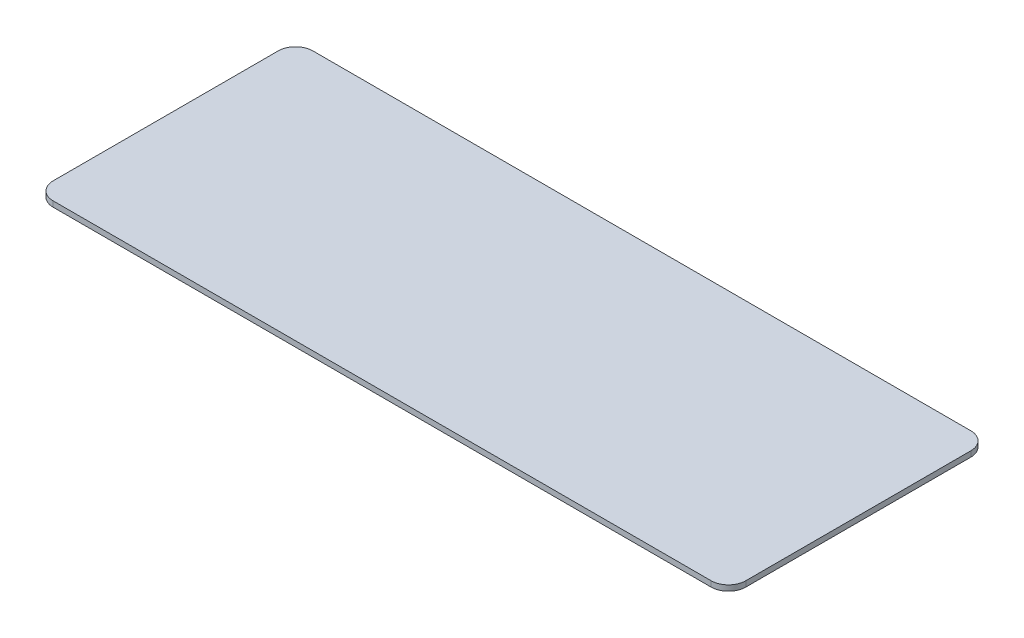
SolidWorks part; units mm, degrees
ref_plane "前视基准面" through (0, 0, 0) normal (0, 0, 1) x (1, 0, 0)
ref_plane "上视基准面" through (0, 0, 0) normal (0, 1, 0) x (1, 0, 0)
ref_plane "右视基准面" through (0, 0, 0) normal (1, 0, 0) x (0, 0, -1)
sketch "草图1" plane through (0, 0, 0) normal (0, 1, 0) x (1, 0, 0)
  line L1 (-100, -37.5) -> (100, -37.5)
  line L2 (-100, -37.5) -> (-100, 37.5)
  line L3 (-100, 37.5) -> (100, 37.5)
  line L4 (100, -37.5) -> (100, 37.5)
  line L5 (-100, -37.5) -> (100, 37.5) construction
  line L6 (-100, 37.5) -> (100, -37.5) construction
  point P0 (0, 0)
  dimension "D1" = 200
  dimension "D2" = 75
extrude "凸台-拉伸1" add sketch "草图1" along normal blind 1.6
fillet "圆角1" radius 5 4 edges at (100, 0.8, 37.5) (100, 0.8, -37.5) (-100, 0.8, -37.5) (-100, 0.8, 37.5)
